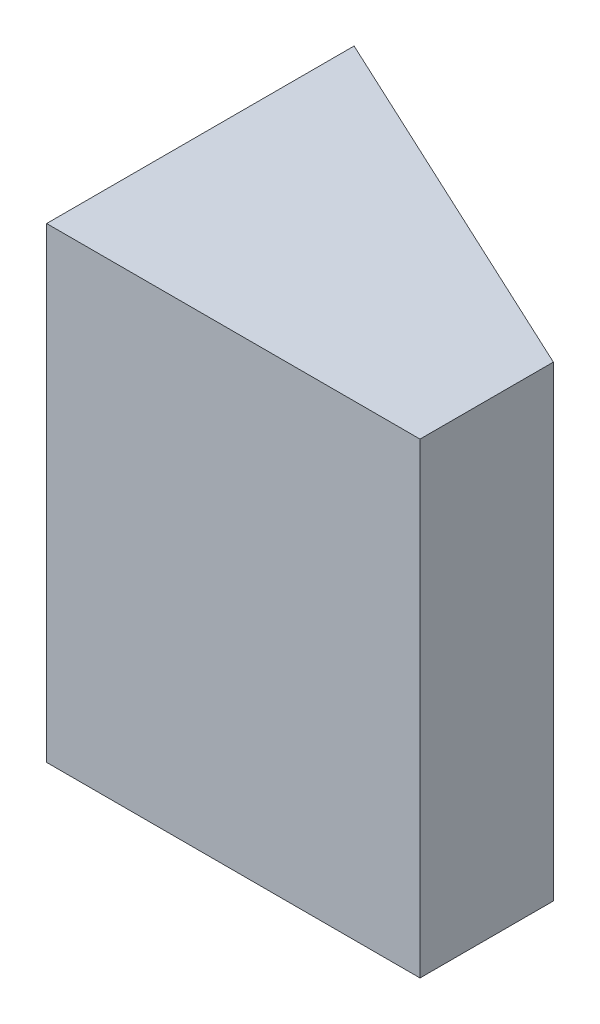
SolidWorks part; units mm, degrees
ref_plane "Front" through (0, 0, 0) normal (0, 0, 1) x (1, 0, 0)
ref_plane "Top" through (0, 0, 0) normal (0, 1, 0) x (1, 0, 0)
ref_plane "Right" through (0, 0, 0) normal (1, 0, 0) x (0, 0, -1)
sketch "Sketch1" plane through (0, 0, 0) normal (0, 1, 0) x (1, 0, 0)
  line L0 (56, 20) -> (0, 46.1132)
  line L1 (0, 0) -> (56, 0)
  line L2 (0, 0) -> (0, 20)
  line L3 (0, 20) -> (56, 20)
  line L4 (56, 0) -> (56, 20)
  line L5 (0, 46.1132) -> (0, 20)
  dimension "D1" = 20
  dimension "D2" = 25
  dimension "D3" = 56
extrude "Boss-Extrude1" add sketch "Sketch1" along normal blind 70 contours L0 L5 L3 | L1 L4 L3 L2
